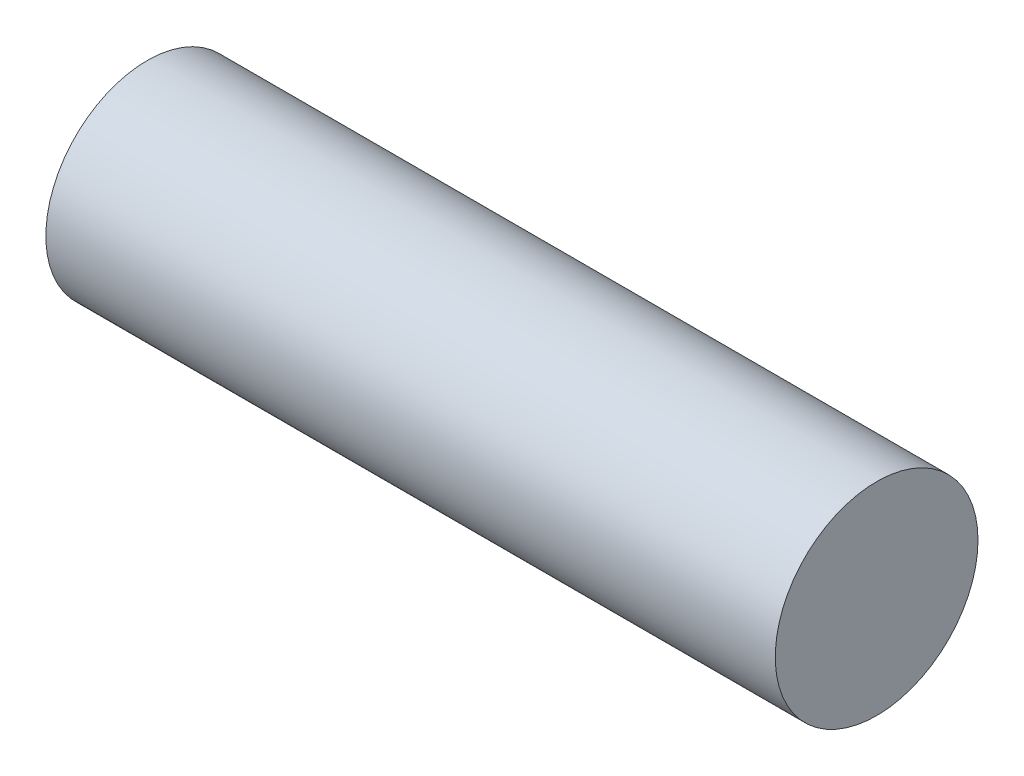
SolidWorks part; units mm, degrees
ref_plane "Front Plane" through (0, 0, 0) normal (0, 0, 1) x (1, 0, 0)
ref_plane "Top Plane" through (0, 0, 0) normal (0, 1, 0) x (1, 0, 0)
ref_plane "Right Plane" through (0, 0, 0) normal (1, 0, 0) x (0, 0, -1)
sketch "Sketch1" plane through (0, 0, 0) normal (1, 0, 0) x (0, 0, -1)
  circle A0 centre (0, 0) radius 2.0828
  dimension "D1" = 4.1656
extrude "Boss-Extrude1" add sketch "Sketch1" along normal blind 14.986 contours A0
